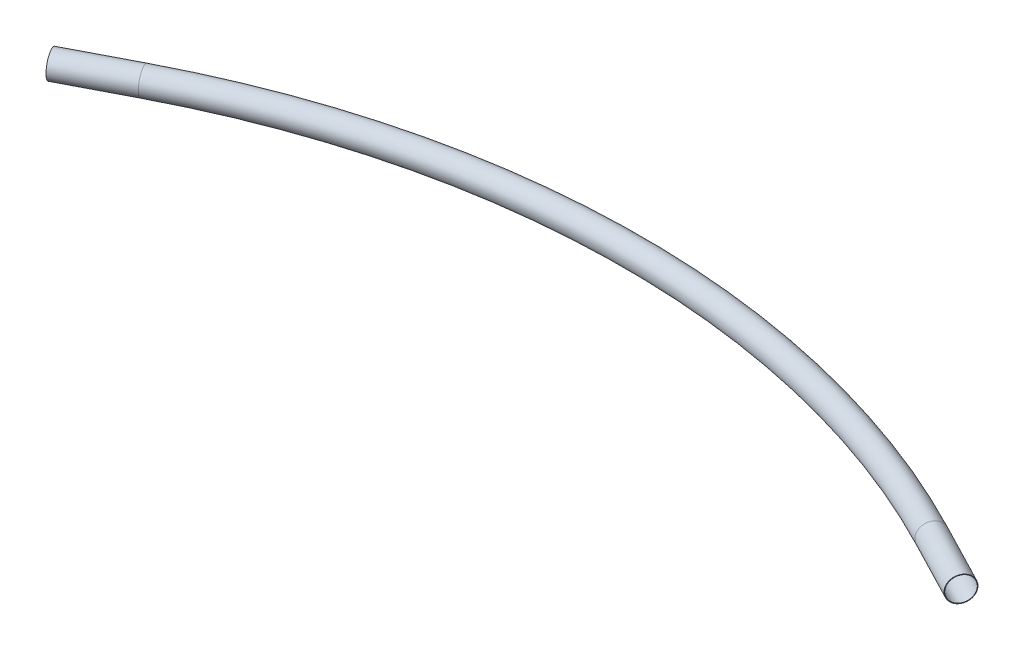
SolidWorks part; units mm, degrees
ref_plane "Front Plane" through (0, 0, 0) normal (0, 0, 1) x (1, 0, 0)
ref_plane "Top Plane" through (0, 0, 0) normal (0, 1, 0) x (1, 0, 0)
ref_plane "Right Plane" through (0, 0, 0) normal (1, 0, 0) x (0, 0, -1)
sketch "Pipe_Definition" plane through (0, 0, 0) normal (0, 1, 0) x (1, 0, 0)
  line L0 (0, 0) -> (0, 641.35) construction
  line L1 (-2630.4875, 0) -> (2630.4875, 0) construction
  line L6 (-2630.4875, 0) -> (-3036.3806, -210.4343)
  line L10 (2630.4875, 0) -> (3036.3806, -210.4343)
  arc A1 (2630.4875, 0) -> (-2630.4875, 0) centre (0, -5073.7777) ccw
  dimension "D1" = 457.2
  dimension "D3" = 5260.975
  dimension "D4" = 2707.544
  dimension "D5" = 6072.7613
  dimension "D2" = 641.35
  dimension "D7" = 5715.1277
  dimension "D6" = 2630.4875
other "Structural Member1"
ref_plane "Plane1" through (2630.4875, 0, 0) normal (-0.8878, 0, -0.4603) x (-0.4603, 0, 0.8878)
sketch "Sketch12" plane through (2630.4875, 0, 0) normal (-0.8878, 0, -0.4603) x (-0.4603, 0, 0.8878)
  circle A0 centre (0, 0) radius 84.1375
  circle A1 centre (0, 0) radius 80.7339
  point P4 (0, 0)
  dimension "D1" = 168.275
  dimension "D2" = 161.4678
equation "\"D2@Sketch12\" = \"D1@Sketch12\" - .134*2"
